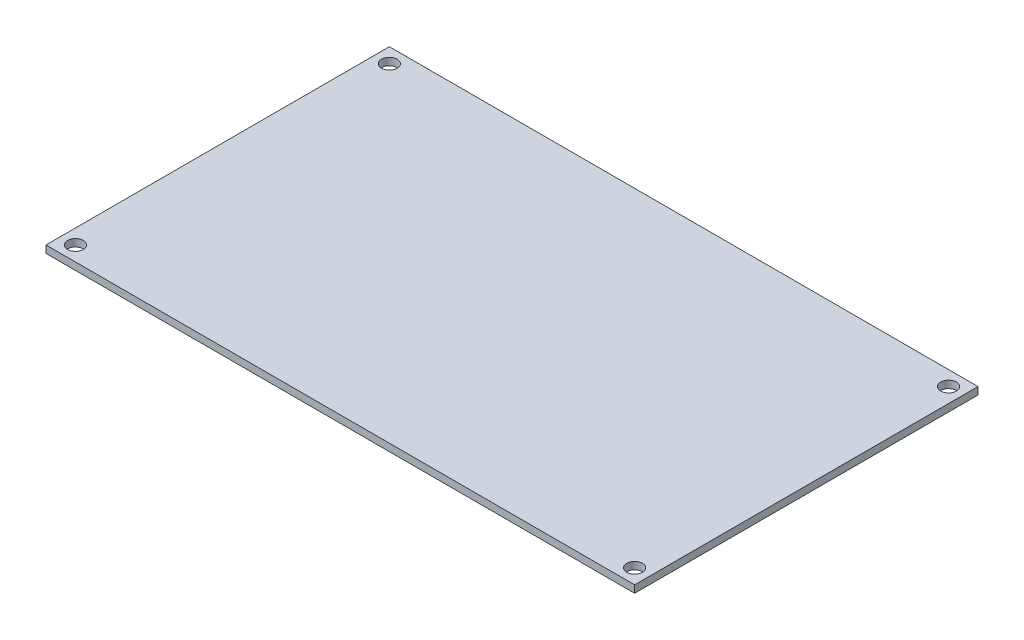
SolidWorks part; units mm, degrees
material "Плата системы питания"
ref_plane "Спереди" through (0, 0, 0) normal (0, 0, 1) x (1, 0, 0)
ref_plane "Сверху" through (0, 0, 0) normal (0, 1, 0) x (1, 0, 0)
ref_plane "Справа" through (0, 0, 0) normal (1, 0, 0) x (0, 0, -1)
sketch "Эскиз1" plane through (0, 0, 0) normal (0, 1, 0) x (1, 0, 0)
  line L1 (-60, 35) -> (60, 35)
  line L2 (-60, 35) -> (-60, -35)
  line L3 (-60, -35) -> (60, -35)
  line L4 (60, 35) -> (60, -35)
extrude "Бобышка-Вытянуть1" add sketch "Эскиз1" along normal blind 1.5
sketch "Эскиз2" plane through (0, 1.5, 0) normal (0, 1, 0) x (1, 0, 0)
  circle A0 centre (-57, 32) radius 1.6
  circle A1 centre (57, -32) radius 1.6
  circle A2 centre (57, 32) radius 1.6
  circle A3 centre (-57, -32) radius 1.6
extrude "Вырез-Вытянуть1" cut sketch "Эскиз2" against normal up to surface (1.5 mm away) up to face at (0, 0, 0)
